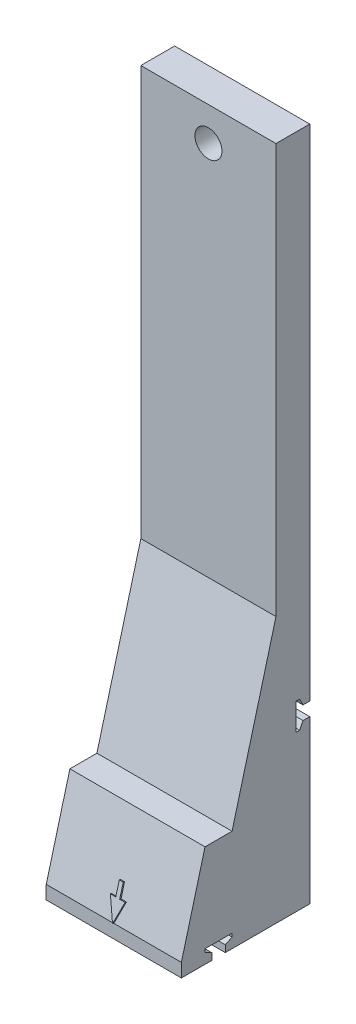
SolidWorks part; units mm, degrees
ref_plane "前视基准面" through (0, 0, 0) normal (0, 0, 1) x (1, 0, 0)
ref_plane "上视基准面" through (0, 0, 0) normal (0, 1, 0) x (1, 0, 0)
ref_plane "右视基准面" through (0, 0, 0) normal (1, 0, 0) x (0, 0, -1)
other "Configuration Table"
sketch "草图1" plane through (1150, 0, 0) normal (1, 0, 0) x (0, 0, -1)
  line L1 (-200, 50) -> (-200, 60)
  line L2 (-200, 60) -> (-182.5, 125.3109)
  line L3 (-182.5, 125.3109) -> (-162.5, 125.3109)
  line L4 (-162.5, 125.3109) -> (-130, 246.6025)
  line L5 (-130, 246.6025) -> (-130, 816.1392)
  line L6 (-130, 816.1392) -> (-105, 816.1392)
  line L7 (-105, 816.1392) -> (-105, 180)
  line L8 (-105, 180) -> (-110, 180)
  line L9 (-110, 180) -> (-112.5, 185)
  line L10 (-112.5, 185) -> (-115, 185)
  line L11 (-115, 185) -> (-115, 165)
  line L12 (-115, 165) -> (-112.5, 165)
  line L13 (-112.5, 165) -> (-110, 170)
  line L14 (-110, 170) -> (-105, 170)
  line L15 (-105, 170) -> (-105, 50)
  line L16 (-105, 50) -> (-167.5, 50)
  line L17 (-167.5, 50) -> (-167.5, 55)
  line L18 (-167.5, 55) -> (-162.5, 57.5)
  line L19 (-162.5, 57.5) -> (-162.5, 60)
  line L20 (-162.5, 60) -> (-182.5, 60)
  line L21 (-182.5, 60) -> (-182.5, 57.5)
  line L22 (-182.5, 57.5) -> (-177.5, 55)
  line L23 (-177.5, 55) -> (-177.5, 50)
  line L24 (-177.5, 50) -> (-200, 50)
  dimension "D1" = 40
  dimension "D2" = 10
  dimension "D3" = 75
  dimension "D4" = 25
extrude "凸台-拉伸1" add sketch "草图1" along normal blind 100
sketch "草图2" plane through (0, 0, 105) normal (0, 0, -1) x (-1, 0, 0)
  line L2 (-1250, 549.7626) -> (-1250, 1004.4219)
  line L3 (-1250, 1004.4219) -> (-1150, 1004.4219)
  line L4 (-1150, 549.7626) -> (-1150, 1004.4219)
  line L6 (-1150, 180) -> (-1150, 816.1392) construction
  line L7 (-1250, 549.7626) -> (-1150, 549.7626)
extrude "切除-拉伸1" cut sketch "草图2" against normal through all both and the other way through all
sketch "草图3" plane through (0, 54.0192, 201.6025) normal (0, 0.2588, 0.9659) x (1, 0, 0)
  line L0 (1200, 6.1917) -> (1200, 58.2787) construction
  line L1 (1250, 6.1917) -> (1150, 6.1917) construction
  line L2 (1200, 6.1917) -> (1194.5404, 21.1917)
  line L3 (1194.5404, 21.1917) -> (1198.5404, 21.1917)
  line L4 (1198.5404, 21.1917) -> (1198.5404, 31.1917)
  line L5 (1198.5404, 31.1917) -> (1201.4596, 31.1917)
  line L6 (1201.4596, 31.1917) -> (1201.4596, 21.1917)
  line L7 (1201.4596, 21.1917) -> (1205.4596, 21.1917)
  line L8 (1205.4596, 21.1917) -> (1200, 6.1917)
  dimension "D1" = 20
  dimension "D2" = 20
  dimension "D3" = 4
  dimension "D4" = 4
  dimension "D5" = 15
  dimension "D6" = 15
  dimension "D7" = 10
extrude "凸台-拉伸2" add sketch "草图3" along normal blind 1
sketch "草图4" plane through (0, 0, 130) normal (0, 0, 1) x (1, 0, 0)
  line L3 (1150, 524.8813) -> (1250, 524.8813) construction
  line L4 (1250, 549.7626) -> (1250, 246.6025) construction
  line L5 (1200, 549.7626) -> (1200, 508.9545) construction
  line L6 (1250, 549.7626) -> (1150, 549.7626) construction
  circle A0 centre (1200, 524.8813) radius 10
  dimension "D1" = 20
extrude "切除-拉伸2" cut sketch "草图4" against normal blind 56
ref_plane "基准面1" through (1200, 0, 0) normal (-1, 0, 0) x (0, 0, 1)
